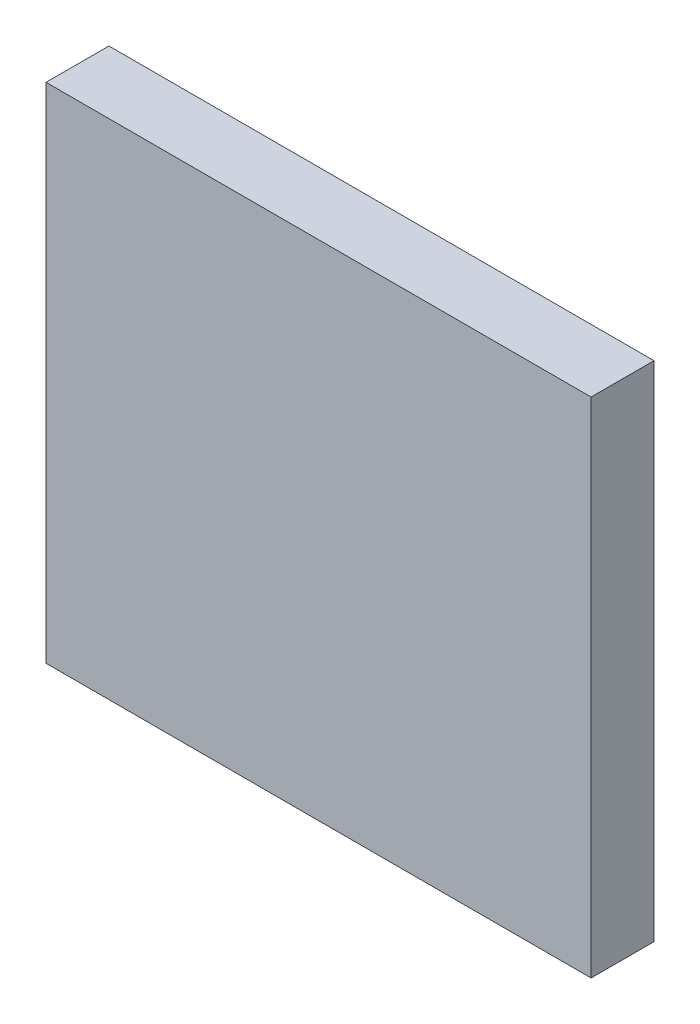
SolidWorks part; units mm, degrees
ref_plane "Спереди" through (0, 0, 0) normal (0, 0, 1) x (1, 0, 0)
ref_plane "Сверху" through (0, 0, 0) normal (0, 1, 0) x (1, 0, 0)
ref_plane "Справа" through (0, 0, 0) normal (1, 0, 0) x (0, 0, -1)
sketch "Эскиз1" plane through (0, 0, 0) normal (0, 0, 1) x (1, 0, 0)
  line L1 (-13, -12) -> (13, -12)
  line L2 (-13, -12) -> (-13, 12)
  line L3 (-13, 12) -> (13, 12)
  line L4 (13, -12) -> (13, 12)
  line L5 (-13, -12) -> (13, 12) construction
  line L6 (-13, 12) -> (13, -12) construction
  point P1 (0, 0)
  dimension "D1" = 24
  dimension "D2" = 26
extrude "Бобышка-Вытянуть1" add sketch "Эскиз1" along normal blind 3
